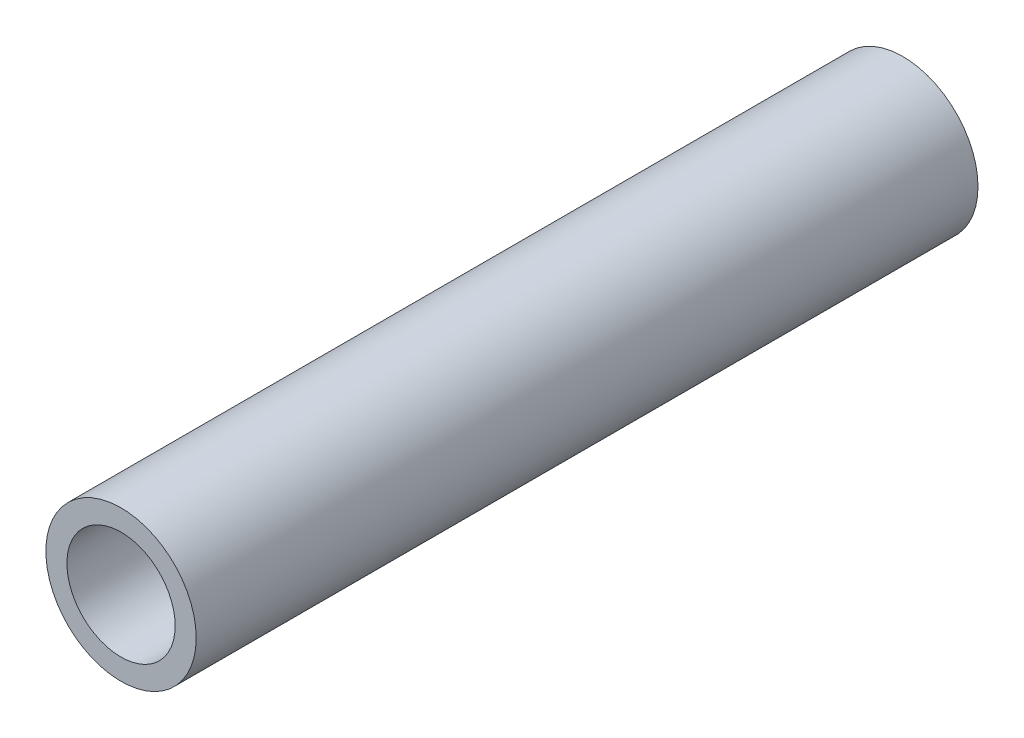
SolidWorks part; units mm, degrees
ref_plane "Спереди" through (0, 0, 0) normal (0, 0, 1) x (1, 0, 0)
ref_plane "Сверху" through (0, 0, 0) normal (0, 1, 0) x (1, 0, 0)
ref_plane "Справа" through (0, 0, 0) normal (1, 0, 0) x (0, 0, -1)
sketch "Эскиз1" plane through (0, 0, 0) normal (0, 0, 1) x (1, 0, 0)
  circle A0 centre (0, 0) radius 4.5
  circle A1 centre (0, 0) radius 6.25
extrude "Бобышка-Вытянуть1" add sketch "Эскиз1" along normal blind 65
